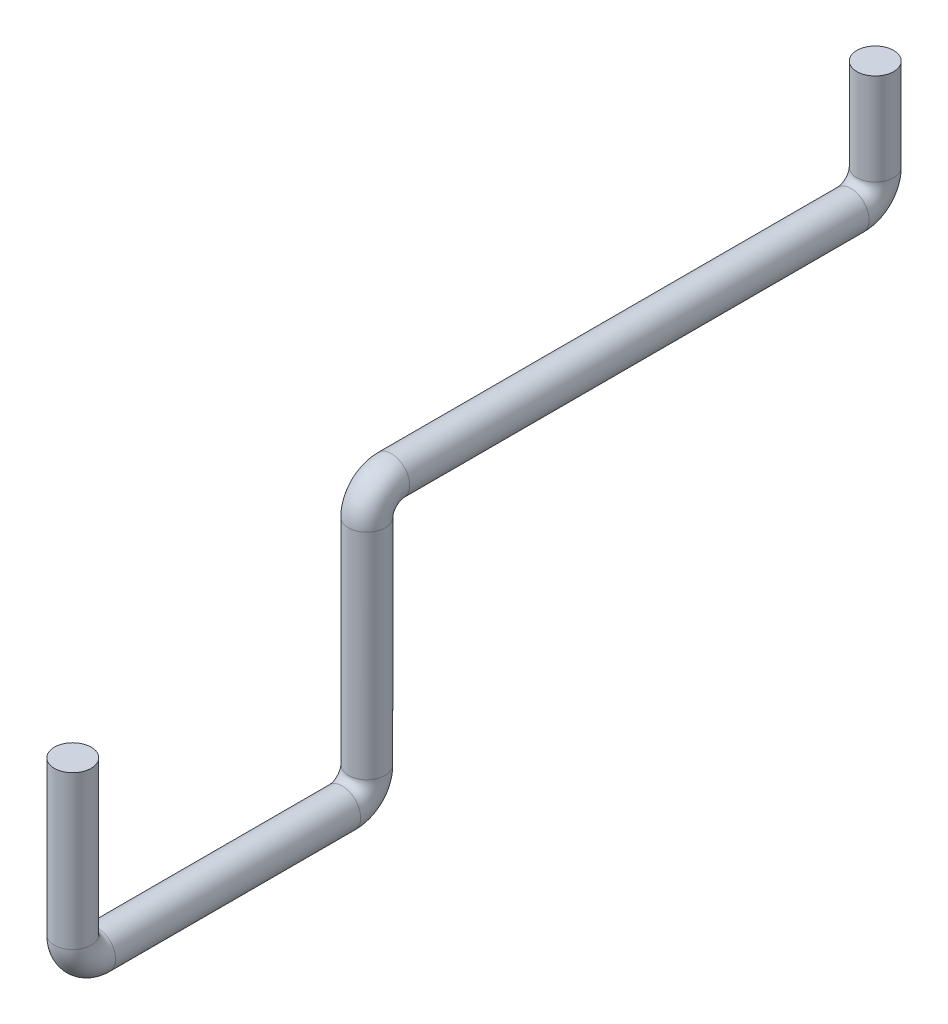
SolidWorks part; units mm, degrees
ref_plane "Front Plane" through (0, 0, 0) normal (0, 0, 1) x (1, 0, 0)
ref_plane "Top Plane" through (0, 0, 0) normal (0, 1, 0) x (1, 0, 0)
ref_plane "Right Plane" through (0, 0, 0) normal (1, 0, 0) x (0, 0, -1)
sketch "Sketch1" plane through (0, 0, 0) normal (1, 0, 0) x (0, 0, -1)
  line L0 (0, 0) -> (0, -5)
  line L1 (0.8, -5.8) -> (8.8, -5.8)
  line L2 (9.6, -5) -> (9.6, 2)
  line L3 (10.4, 2.8) -> (25.4, 2.8)
  line L4 (26.2, 3.6) -> (26.2, 6.6)
  arc A0 (0, -5) -> (0.8, -5.8) centre (0.8, -5) ccw
  arc A1 (8.8, -5.8) -> (9.6, -5) centre (8.8, -5) ccw
  arc A2 (9.6, 2) -> (10.4, 2.8) centre (10.4, 2) cw
  arc A3 (25.4, 2.8) -> (26.2, 3.6) centre (25.4, 3.6) ccw
  dimension "D2" = 0.8
  dimension "D4" = 0.8
  dimension "D6" = 0.8
  dimension "D8" = 0.8
  dimension "D1" = 5
  dimension "D3" = 8
  dimension "D5" = 7
  dimension "D7" = 15
  dimension "D9" = 3
sweep "Sweep1" add path "Sketch1" circular profile diameter 1.2 parameters "D3"=1.2
